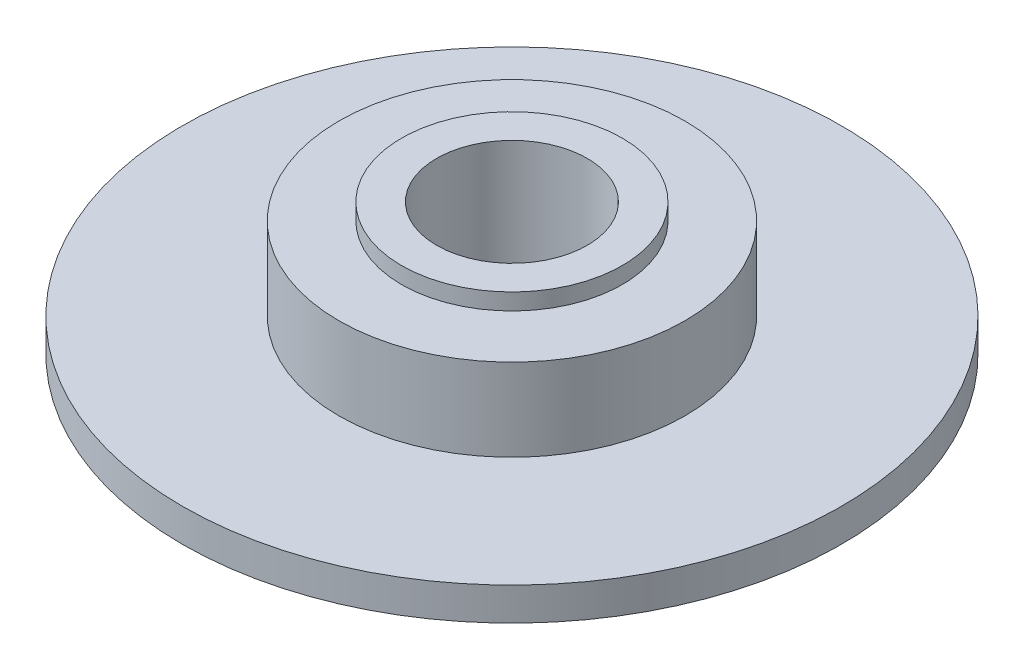
SolidWorks part; units mm, degrees
ref_plane "Front Plane" through (0, 0, 0) normal (0, 0, 1) x (1, 0, 0)
ref_plane "Top Plane" through (0, 0, 0) normal (0, 1, 0) x (1, 0, 0)
ref_plane "Right Plane" through (0, 0, 0) normal (1, 0, 0) x (0, 0, -1)
sketch "Sketch1" plane through (0, 0, 0) normal (0, 1, 0) x (1, 0, 0)
  circle A0 centre (0, 0) radius 20
  circle A1 centre (0, 0) radius 4.572
  dimension "D1" = 40
  dimension "D2" = 9.144
extrude "Boss-Extrude1" add sketch "Sketch1" along normal blind 2
sketch "Sketch2" plane through (0, 2, 0) normal (0, 1, 0) x (1, 0, 0)
  circle A0 centre (0, 0) radius 10.5
  circle A1 centre (0, 0) radius 4.572
  dimension "D1" = 21
extrude "Boss-Extrude2" add sketch "Sketch2" along normal blind 5
sketch "Sketch3" plane through (0, 7, 0) normal (0, 1, 0) x (1, 0, 0)
  circle A0 centre (0, 0) radius 6.7
  circle A1 centre (0, 0) radius 4.572
  dimension "D1" = 13.4
extrude "Boss-Extrude3" add sketch "Sketch3" along normal blind 1
